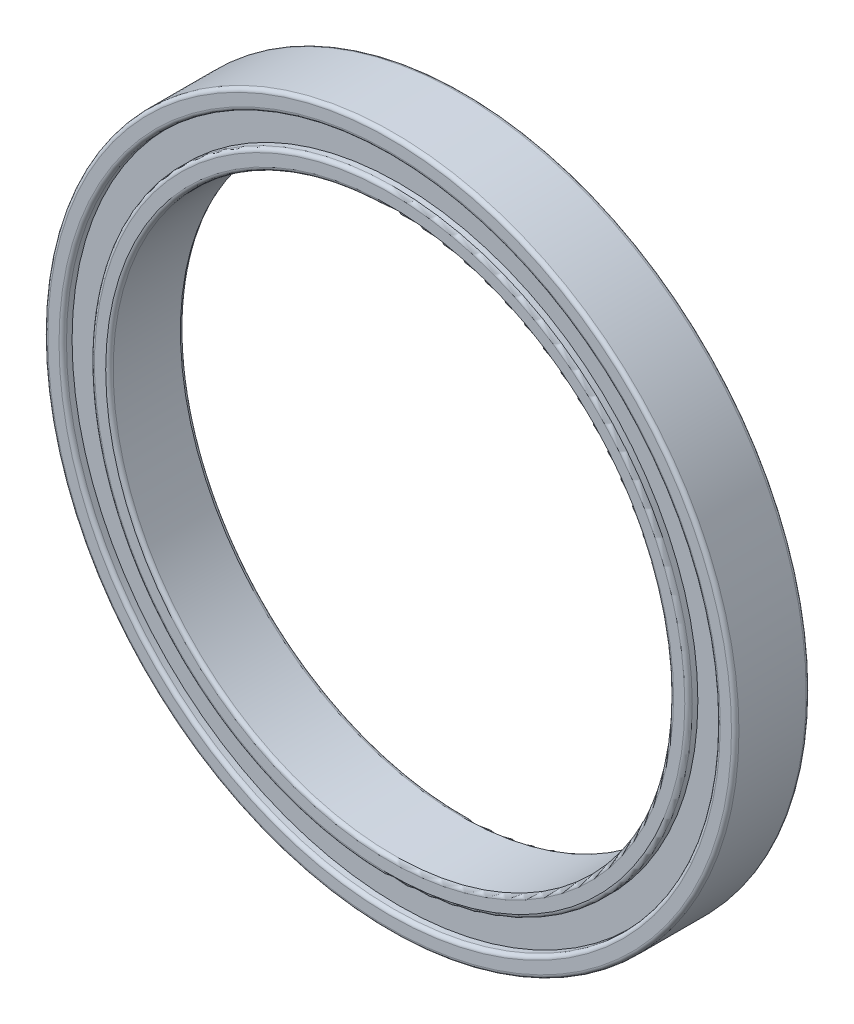
SolidWorks part; units mm, degrees
ref_plane "Front Plane" through (0, 0, 0) normal (0, 0, 1) x (1, 0, 0)
ref_plane "Top Plane" through (0, 0, 0) normal (0, 1, 0) x (1, 0, 0)
ref_plane "Right Plane" through (0, 0, 0) normal (1, 0, 0) x (0, 0, -1)
sketch "Sketch1" plane through (0, 0, 0) normal (0, 0, 1) x (1, 0, 0)
  circle A0 centre (0, 0) radius 18.5
  circle A1 centre (0, 0) radius 15
  dimension "D1" = 37
  dimension "D2" = 30
extrude "Extrude1" add sketch "Sketch1" along normal blind 4
sketch "Sketch2" plane through (0, 0, 4) normal (0, 0, 1) x (1, 0, 0)
  circle A0 centre (0, 0) radius 16
  circle A1 centre (0, 0) radius 17.5
  dimension "D1" = 32
  dimension "D2" = 35
extrude "Cut-Extrude1" cut sketch "Sketch2" against normal blind 0.5
sketch "Sketch3" plane through (0, 0, 0) normal (0, 0, -1) x (-1, 0, 0)
  circle A0 centre (0, 0) radius 16
  circle A1 centre (0, 0) radius 17.5
  dimension "D1" = 32
  dimension "D2" = 35
extrude "Cut-Extrude2" cut sketch "Sketch3" against normal blind 0.5
fillet "Fillet1" radius 0.2 8 edges at (17.5, 0, 4) (16, 0, 4) (18.5, 0, 0) (-17.5, 0, 0) (-16, 0, 0) (18.5, 0, 4) (15, 0, 0) (15, 0, 4)
